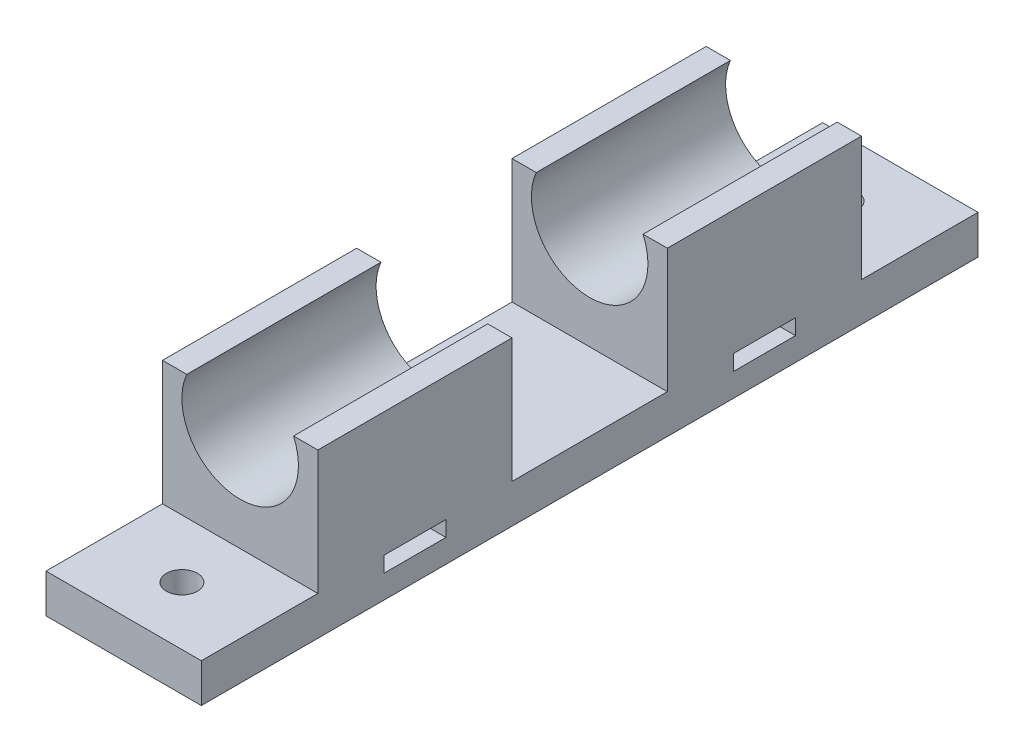
SolidWorks part; units mm, degrees
material "ABS"
ref_plane "Plano frontal" through (0, 0, 0) normal (0, 0, 1) x (1, 0, 0)
ref_plane "Plano superior" through (0, 0, 0) normal (0, 1, 0) x (1, 0, 0)
ref_plane "Plano direito" through (0, 0, 0) normal (1, 0, 0) x (0, 0, -1)
sketch "Esboço1" plane through (0, 0, 0) normal (1, 0, 0) x (0, 0, -1)
  line L0 (0, 14) -> (0, 0) construction
  line L1 (-35, 21) -> (-10, 21)
  line L2 (-35, 21) -> (-35, 0)
  line L3 (-35, 0) -> (35, 0)
  line L4 (35, 21) -> (35, 0)
  line L5 (18.5, 3) -> (26.5, 5) construction
  line L6 (-18.5, 5) -> (-26.5, 5)
  line L7 (-18.5, 5) -> (-18.5, 3)
  line L8 (-18.5, 3) -> (-26.5, 3)
  line L9 (-10, 21) -> (-10, 5)
  line L10 (-26.5, 5) -> (-26.5, 3)
  line L11 (-18.5, 5) -> (-26.5, 3) construction
  line L12 (-18.5, 3) -> (-26.5, 5) construction
  line L13 (18.5, 5) -> (26.5, 3) construction
  line L14 (-10, 5) -> (10, 5)
  line L15 (10, 21) -> (10, 5)
  line L16 (10, 21) -> (35, 21)
  line L17 (26.5, 5) -> (26.5, 3)
  line L18 (18.5, 3) -> (26.5, 3)
  line L19 (18.5, 5) -> (18.5, 3)
  line L20 (18.5, 5) -> (26.5, 5)
  point P0 (0, 0)
  point P1 (-22.5, 4)
  point P18 (0, 5)
  point P21 (22.5, 4)
  point P24 (-22.5, 21)
  dimension "D1" = 8
  dimension "D2" = 21
  dimension "D3" = 70
  dimension "D4" = 2
  dimension "D5" = 25
  dimension "D6" = 5
  dimension "D7" = 4
extrude "Ressalto-extrusão1" add sketch "Esboço1" along normal mid plane 20
sketch "Esboço2" plane through (0, 0, 35) normal (0, 0, 1) x (1, 0, 0)
  line L0 (10, 21) -> (-10, 21) construction
  line L1 (-6.8739, 21) -> (6.8739, 21)
  arc A0 (-6.8739, 21) -> (6.8739, 21) centre (0, 18) ccw
  point P0 (0, 18)
  point P20 (0, 21)
  dimension "D1" = 15
  dimension "D2" = 3
extrude "Corte-extrusão1" cut sketch "Esboço2" against normal up to surface (70 mm away) up to face at (0, 10.5, -35)
sketch "Esboço4" plane through (0, 5, 0) normal (0, 1, 0) x (1, 0, 0)
  line L1 (-10, 0) -> (10, 0) construction
  line L2 (-10, 35) -> (10, 35)
  line L3 (-10, 35) -> (-10, 50)
  line L4 (-10, 50) -> (10, 50)
  line L5 (10, -35) -> (10, -50)
  line L6 (10, 35) -> (10, 50)
  line L7 (-10, -50) -> (10, -50)
  line L8 (-10, 10) -> (-10, -10) construction
  line L9 (10, 10) -> (10, -10) construction
  line L10 (-10, -35) -> (-10, -50)
  line L11 (-10, -35) -> (10, -35)
  line L12 (10, -35) -> (10, 35) construction
  circle A0 centre (0, 42.5) radius 2
  circle A1 centre (0, -42.5) radius 2
  point P13 (0, 50)
  dimension "D3" = 7.5
  dimension "D2" = 4
  dimension "D1" = 100
extrude "Ressalto-extrusão2" add sketch "Esboço4" against normal up to surface (5 mm away) up to face at (0, 0, 0)
